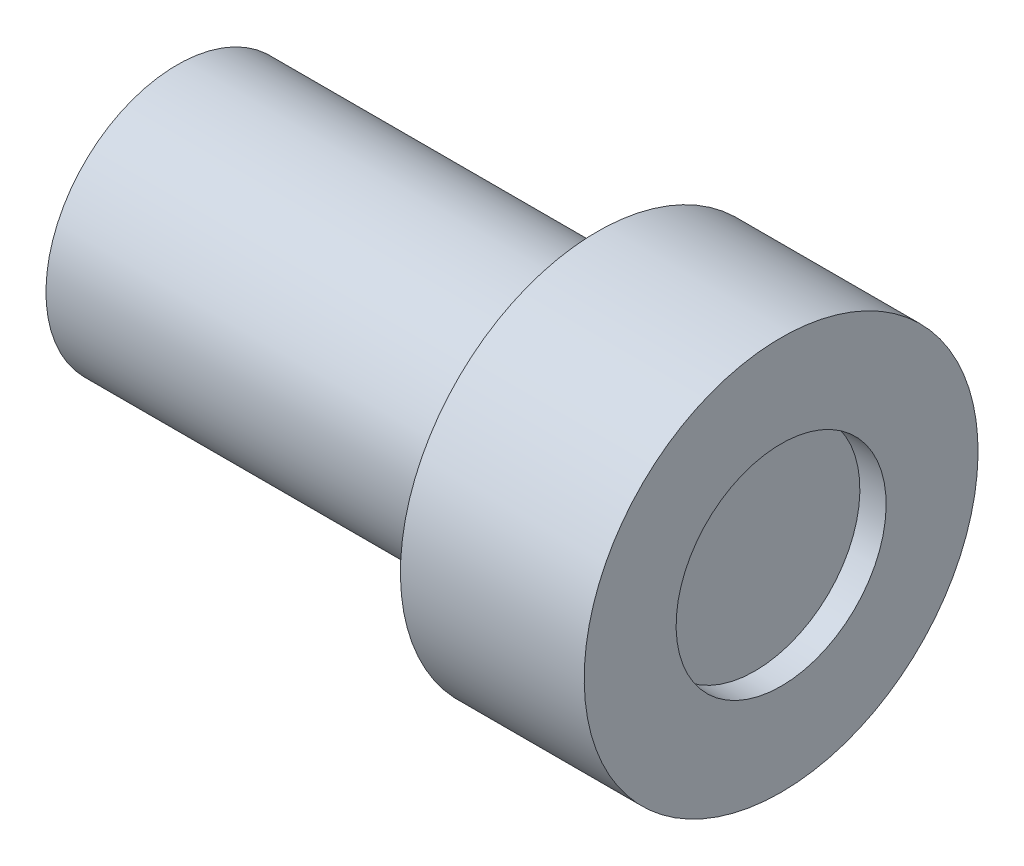
SolidWorks part; units mm, degrees
ref_plane "Plano frontal" through (0, 0, 0) normal (1, 0, 0) x (0, 1, 0)
ref_plane "Plano superior" through (0, 0, 0) normal (0, 0, 1) x (0, 1, 0)
ref_plane "Plano direito" through (0, 0, 0) normal (0, 1, 0) x (-1, 0, 0)
sketch "Esboço1" plane through (0, 0, 0) normal (0, 0, 1) x (0, 1, 0)
  line L0 (0, 5.5) -> (-2.5, 5.5)
  line L1 (-2.5, 5.5) -> (-2.5, -2.5)
  line L2 (-2.5, -2.5) -> (-3.75, -2.5)
  line L3 (-3.75, -2.5) -> (-3.75, -3.5606)
  line L5 (-3.75, -3.5606) -> (-3.75, -6)
  line L6 (-3.75, -6) -> (-2, -6)
  line L7 (-2, -6) -> (-2, -5.5)
  line L8 (-2, -5.5) -> (0, -5.5)
  line L9 (0, 5.5) -> (0, -5.5) construction
  line L10 (0, 5.5) -> (0, -5.5)
  point P2 (0, 0)
  dimension "D1" = 2.5
  dimension "D4" = 2
  dimension "D5" = 1.75
  dimension "D6" = 0.5
  dimension "D7" = 11
revolve "Revolução1" add sketch "Esboço1" angle 360 about L9
sketch "Esboço2" plane through (-5.5, 0, 0) normal (-1, 0, 0) x (0, 0, 1)
  line L4 (-0.664, -1.15) -> (1.3279, 0)
  line L5 (1.3279, 0) -> (-0.664, 1.15)
  line L6 (-0.664, 1.15) -> (-0.664, -1.15)
  line L7 (-0.664, 0.6) -> (-1.864, 0.6)
  line L8 (-0.664, 0.6) -> (-0.664, -0.6)
  line L9 (-0.664, -0.6) -> (-1.864, -0.6)
  line L10 (-1.864, 0.6) -> (-1.864, -0.6)
  line L11 (-0.664, 0.6) -> (-1.864, -0.6) construction
  line L12 (-0.664, -0.6) -> (-1.864, 0.6) construction
  circle A0 centre (0, 0) radius 0.664 construction
  point P0 (-1.264, 0)
  point P11 (-0.664, 0)
  point P12 (-0.664, 0)
  dimension "D1" = 2.3
  dimension "D2" = 1.2
  dimension "D3" = 1.2
extrude "Corte-extrusão1" cut sketch "Esboço2" against normal blind 1 contours L7 L10 L9 L6
